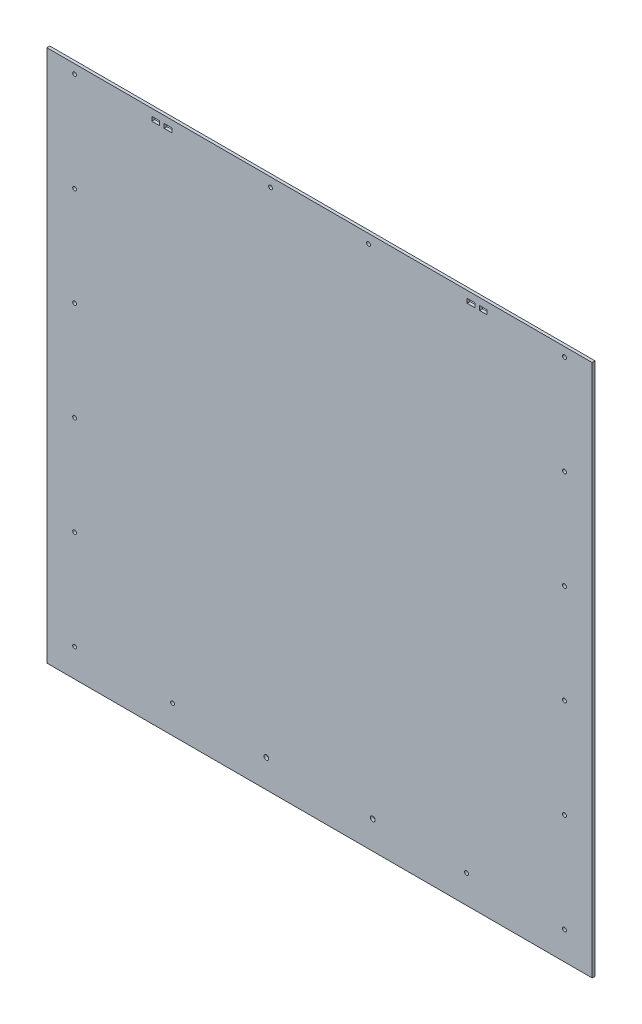
SolidWorks part; units mm, degrees
material "PC Высокая вязкость"
ref_plane "Спереди" through (0, 0, 0) normal (0, 0, 1) x (1, 0, 0)
ref_plane "Сверху" through (0, 0, 0) normal (0, 1, 0) x (1, 0, 0)
ref_plane "Справа" through (0, 0, 0) normal (1, 0, 0) x (0, 0, -1)
sketch "Эскиз1" plane through (0, 0, 0) normal (0, 0, 1) x (1, 0, 0)
  line L1 (0, 0) -> (748, 0)
  line L2 (0, 0) -> (0, -731.05)
  line L3 (0, -731.05) -> (748, -731.05)
  line L4 (748, 0) -> (748, -731.05)
  dimension "D1" = 748
  dimension "D2" = 731.05
extrude "Бобышка-Вытянуть1" add sketch "Эскиз1" along normal blind 4
sketch "Эскиз2" plane through (0, 0, 4) normal (0, 0, 1) x (1, 0, 0)
  line L0 (748, 0) -> (0, 0) construction
  line L1 (144, -9.57) -> (154.5, -9.57)
  line L2 (144, -9.57) -> (144, -15.37)
  line L3 (144, -15.37) -> (154.5, -15.37)
  line L4 (154.5, -9.57) -> (154.5, -15.37)
  line L5 (161, -9.57) -> (171.5, -9.57)
  line L6 (161, -9.57) -> (161, -15.37)
  line L7 (161, -15.37) -> (171.5, -15.37)
  line L8 (171.5, -9.57) -> (171.5, -15.37)
  line L9 (0, 0) -> (0, -731.05) construction
  line L10 (374, -257.5105) -> (374, -50257.5105) construction
  line L11 (576.5, -9.57) -> (576.5, -15.37)
  line L12 (587, -15.37) -> (576.5, -15.37)
  line L13 (587, -9.57) -> (587, -15.37)
  line L14 (587, -9.57) -> (576.5, -9.57)
  line L15 (593.5, -9.57) -> (593.5, -15.37)
  line L16 (604, -15.37) -> (593.5, -15.37)
  line L17 (604, -9.57) -> (604, -15.37)
  line L18 (604, -9.57) -> (593.5, -9.57)
  point P14 (374, 0)
  dimension "D1" = 10.5
  dimension "D2" = 6.5
  dimension "D3" = 10.5
  dimension "D4" = 5.8
  dimension "D5" = 9.57
  dimension "D6" = 144
  dimension "D7" = 202.5
extrude "Вырез-Вытянуть1" cut sketch "Эскиз2" against normal through all
sketch "Эскиз4" plane through (0, -727.05, 4) normal (0, 0, -1) x (1, 0, 0)
  line L0 (374, 4) -> (374, -49996) construction
  line L1 (0, 4) -> (748, 4) construction
  line L2 (748, -727.05) -> (0, -727.05) construction
  circle A0 centre (301, -34.58) radius 3.25
  circle A1 centre (447, -34.58) radius 3.25
  point P8 (374, -727.05)
  dimension "D1" = 6.5
  dimension "D2" = 6.5
  dimension "D3" = 146
  dimension "D4" = 73
  dimension "D5" = 38.58
extrude "Вырез-Вытянуть2" cut sketch "Эскиз4" along normal through all
sketch "Эскиз5" plane through (0, 0, 0) normal (0, 0, -1) x (-1, 0, 0)
  line L0 (-710, -12.47) -> (-575.6, -12.47) construction
  line L1 (-38, -12.47) -> (-710, -12.47) construction
  line L2 (-710, -12.47) -> (-710, -148.47) construction
  line L3 (-710, -692.47) -> (-710, -12.47) construction
  line L4 (-38, -12.47) -> (-38, -148.47) construction
  line L5 (-38, -692.47) -> (-710, -692.47) construction
  line L6 (-748, -731.05) -> (-748, 0) construction
  line L7 (-748, 0) -> (0, 0) construction
  line L8 (0, -731.05) -> (-748, -731.05) construction
  line L9 (-38, -692.47) -> (-38, -12.47) construction
  line L10 (0, 0) -> (0, -731.05) construction
  line L11 (-710, -692.47) -> (-575.6, -692.47) construction
  circle A1 centre (-710, -12.47) radius 2.6
  circle A2 centre (-441.2, -12.47) radius 2.6
  circle A3 centre (-306.8, -12.47) radius 2.6
  circle A5 centre (-38, -12.47) radius 2.6
  circle A6 centre (-575.6, -12.47) radius 2.6 [skipped]
  circle A7 centre (-172.4, -12.47) radius 2.6 [skipped]
  circle A8 centre (-710, -148.47) radius 2.6
  circle A9 centre (-710, -284.47) radius 2.6
  circle A10 centre (-710, -420.47) radius 2.6
  circle A11 centre (-710, -556.47) radius 2.6
  circle A12 centre (-710, -692.47) radius 2.6
  circle A24 centre (-575.6, -692.47) radius 2.6
  circle A27 centre (-172.4, -692.47) radius 2.6
  circle A28 centre (-306.8, -692.47) radius 2.6 [skipped]
  circle A29 centre (-441.2, -692.47) radius 2.6 [skipped]
  circle A30 centre (-38, -148.47) radius 2.6
  circle A31 centre (-38, -284.47) radius 2.6
  circle A32 centre (-38, -420.47) radius 2.6
  circle A33 centre (-38, -556.47) radius 2.6
  circle A34 centre (-38, -692.47) radius 2.6
  dimension "D5" = 5.2
  dimension "D6" = 6
  dimension "D1" = 38
  dimension "D2" = 12.47
  dimension "D3" = 38.58
  dimension "D4" = 38
  dimension "D7" = 134.4
  dimension "D9" = 136
  dimension "D14" = 134.4
  dimension "D11" = 136
  dimension "D8" = 6
  dimension "D13" = 5
  dimension "D10" = 6
extrude "Вырез-Вытянуть3" cut sketch "Эскиз5" against normal through all
